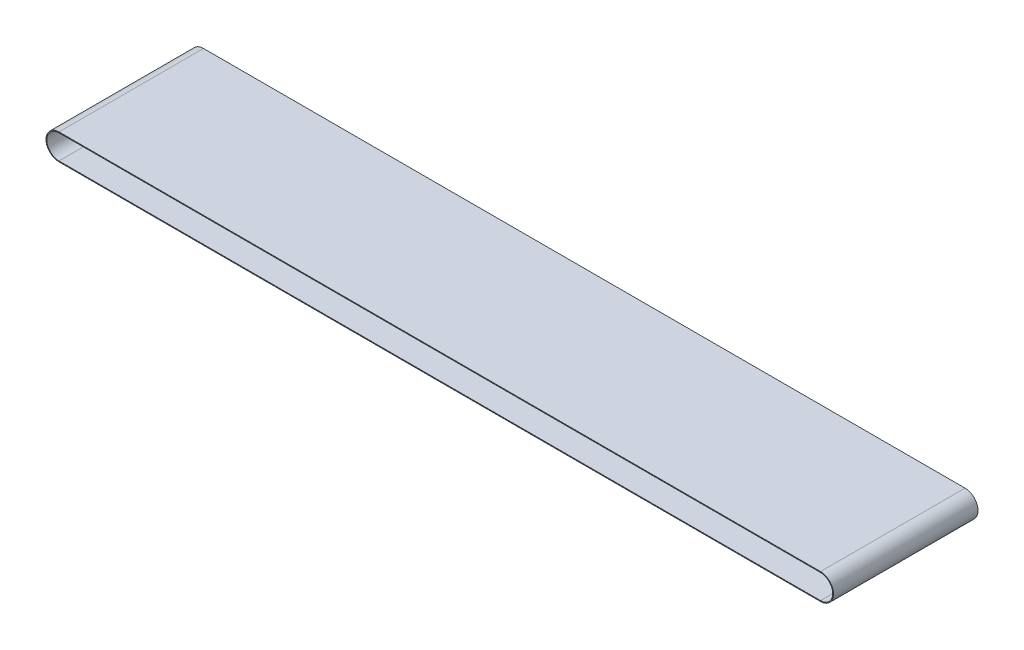
SolidWorks part; units mm, degrees
ref_plane "Alzado" through (0, 0, 0) normal (0, 0, 1) x (1, 0, 0)
ref_plane "Planta" through (0, 0, 0) normal (0, 1, 0) x (1, 0, 0)
ref_plane "Vista lateral" through (0, 0, 0) normal (1, 0, 0) x (0, 0, -1)
sketch "Croquis1" plane through (0, 0, 0) normal (0, 1, 0) x (1, 0, 0)
  line L1 (242.5, -44.5) -> (-242.5, -44.5)
  line L2 (242.5, -44.5) -> (242.5, 44.5)
  line L3 (242.5, 44.5) -> (-242.5, 44.5)
  line L4 (-242.5, -44.5) -> (-242.5, 44.5)
  line L5 (242.5, -44.5) -> (-242.5, 44.5) construction
  line L6 (242.5, 44.5) -> (-242.5, -44.5) construction
  point P0 (0, 0)
extrude "Saliente-Extruir1" add sketch "Croquis1" along normal blind 16
sketch "Croquis2" plane through (0, 0, 44.5) normal (0, 0, 1) x (1, 0, 0)
  line L0 (-242.5, 8) -> (-234.5, 8) construction
  line L1 (234.4995, 15.5) -> (-234.5, 15.5)
  line L2 (-242.5, 16) -> (-242.5, 0) construction
  line L4 (-242.5, 0) -> (-234.5, 0)
  line L5 (-234.5, 15.5) -> (-234.5, 0.5)
  line L6 (-234.5, 0.5) -> (234.4995, 0.5)
  circle A0 centre (-234.5, 8) radius 7.5
  circle A1 centre (-234.5, 8) radius 8
  circle A2 centre (-234.5, 8) radius 7.5
  arc A4 (234.4995, 0.5) -> (234.4995, 15.5) centre (234.4995, 8) ccw
  line M1 (-242.5, 0) -> (242.5, 0)
  line M3 (242.5, 16) -> (-242.5, 16)
  line M4 (-242.5, 16) -> (-242.5, 0)
extrude "Cortar-Extruir2" cut sketch "Croquis2" against normal blind 89 contours A1 M4 M1 | A1 M3 M4
sketch "Croquis3" plane through (0, 0, 44.5) normal (0, 0, 1) x (1, 0, 0)
  line L0 (242.5, 8) -> (234.5, 8) construction
  line L1 (242.5, 16) -> (242.5, 0) construction
  line L2 (234.5, 16) -> (242.5, 16)
  line L3 (242.5, 16) -> (242.5, 8)
  line L4 (242.5, 8) -> (242.5, 0)
  line L5 (242.5, 0) -> (234.5, 0)
  circle A0 centre (234.5, 8) radius 8
  circle A1 centre (234.5, 8) radius 7.5
  line M1 (242.5, 16) -> (-234.5, 16)
  line M3 (-234.5, 0) -> (242.5, 0)
  line M4 (242.5, 0) -> (242.5, 16)
extrude "Cortar-Extruir3" cut sketch "Croquis3" against normal blind 89 contours A0 M4 M1 | A0 M3 M4
sketch "Croquis4" plane through (0, 0, 44.5) normal (0, 0, 1) x (1, 0, 0)
  line L0 (-234.5, 15.5) -> (234.5, 15.5)
  line L1 (234.5, 0.5) -> (-234.5, 0.5)
  arc A0 (-234.5, 15.5) -> (-234.5, 0.5) centre (-234.5, 8) ccw
  arc A1 (234.5, 0.5) -> (234.5, 15.5) centre (234.5, 8) ccw
extrude "Cortar-Extruir4" cut sketch "Croquis4" against normal blind 89
